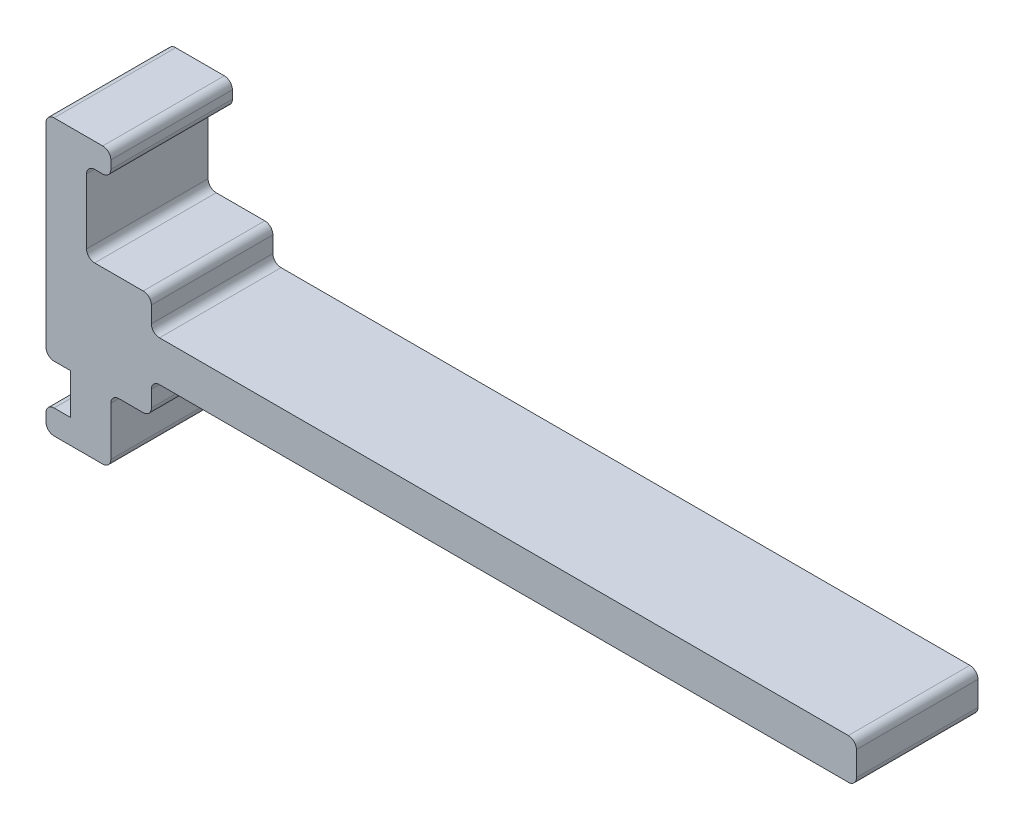
SolidWorks part; units mm, degrees
ref_plane "Front Plane" through (0, 0, 0) normal (0, 0, 1) x (1, 0, 0)
ref_plane "Top Plane" through (0, 0, 0) normal (0, 1, 0) x (1, 0, 0)
ref_plane "Right Plane" through (0, 0, 0) normal (1, 0, 0) x (0, 0, -1)
sketch "Sketch1" plane through (0, 0, 0) normal (0, 0, 1) x (1, 0, 0)
  line L0 (-50, 2.5) -> (-50, 18.5)
  line L2 (-50, 2.5) -> (-50, -2.5)
  line L4 (50, 1.5) -> (50, -1.5)
  line L5 (-49, 19.5) -> (-45, 19.5)
  line L6 (-45, 19.5) -> (-43, 19.5)
  line L7 (-42, 18.5) -> (-42, 17.5)
  line L8 (-43, 16.5) -> (-44, 16.5)
  line L9 (-45, 15.5) -> (-45, 7.5)
  line L10 (-44, 6.5) -> (-38, 6.5)
  line L11 (-37, 5.5) -> (-37, 3.5)
  line L12 (-42, -7.5) -> (-42, -13.5)
  line L13 (-37, -3.5) -> (-37, -5.5)
  line L14 (-38, -6.5) -> (-41, -6.5)
  line L15 (-50, -2.5) -> (-50, -5.5)
  line L16 (-49, -6.5) -> (-47, -6.5)
  line L17 (-47, -6.5) -> (-47, -11.5)
  line L18 (-47, -11.5) -> (-49, -11.5)
  line L19 (-50, -12.5) -> (-50, -13.5)
  line L20 (-49, -14.5) -> (-43, -14.5)
  line L21 (-36, 2.5) -> (49, 2.5)
  line L22 (-36, -2.5) -> (49, -2.5)
  arc A0 (50, -1.5) -> (49, -2.5) centre (49, -1.5) cw
  arc A1 (50, 1.5) -> (49, 2.5) centre (49, 1.5) ccw
  arc A2 (-45, 7.5) -> (-44, 6.5) centre (-44, 7.5) ccw
  arc A3 (-37, 5.5) -> (-38, 6.5) centre (-38, 5.5) ccw
  arc A4 (-37, 3.5) -> (-36, 2.5) centre (-36, 3.5) ccw
  arc A5 (-37, -3.5) -> (-36, -2.5) centre (-36, -3.5) cw
  arc A6 (-37, -5.5) -> (-38, -6.5) centre (-38, -5.5) cw
  arc A7 (-41, -6.5) -> (-42, -7.5) centre (-41, -7.5) ccw
  arc A8 (-42, -13.5) -> (-43, -14.5) centre (-43, -13.5) cw
  arc A9 (-49, -14.5) -> (-50, -13.5) centre (-49, -13.5) cw
  arc A10 (-50, -12.5) -> (-49, -11.5) centre (-49, -12.5) cw
  arc A11 (-49, -6.5) -> (-50, -5.5) centre (-49, -5.5) cw
  arc A12 (-50, 18.5) -> (-49, 19.5) centre (-49, 18.5) cw
  arc A13 (-44, 16.5) -> (-45, 15.5) centre (-44, 15.5) ccw
  arc A14 (-43, 16.5) -> (-42, 17.5) centre (-43, 17.5) ccw
  arc A15 (-42, 18.5) -> (-43, 19.5) centre (-43, 18.5) ccw
  point P0 (0, 0)
  point P33 (-37, 2.5)
extrude "Boss-Extrude1" add sketch "Sketch1" along normal mid plane 15 contours L21 A1 L4 A0 L22 A5 L13 A6 L14 A7 L12 A8 L20 A9 L19 A10 L18 L17 L16 A11 L15 L2 L0 A12 L5 L6 A15 L7 A14 L8 A13 L9 A2 L10 A3 L11 A4
